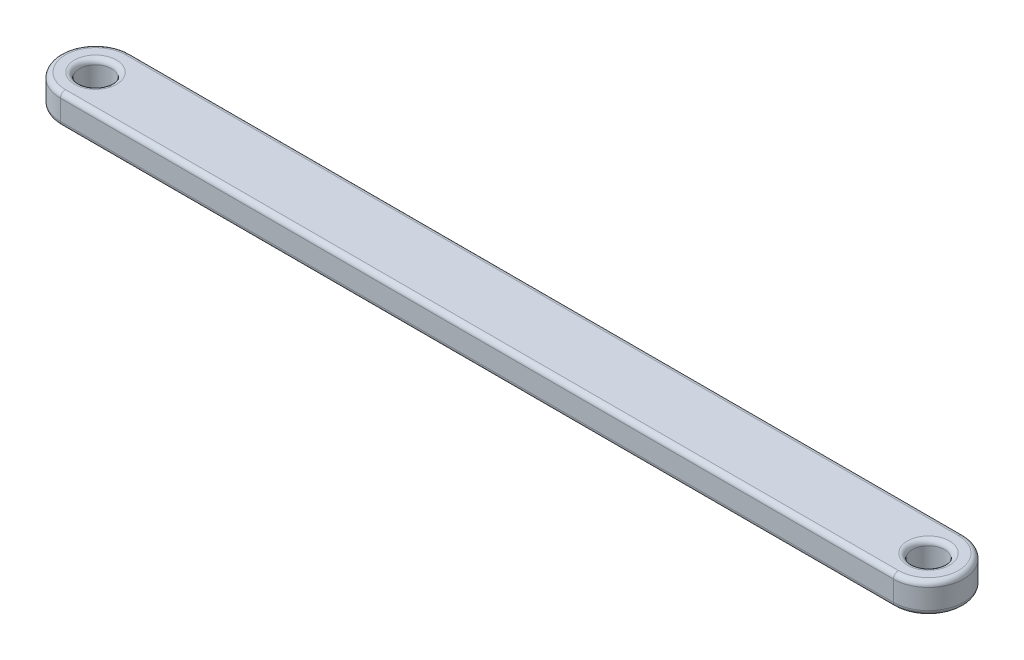
SolidWorks part; units mm, degrees
ref_plane "Front Plane" through (0, 0, 0) normal (0, 0, 1) x (1, 0, 0)
ref_plane "Top Plane" through (0, 0, 0) normal (0, 1, 0) x (1, 0, 0)
ref_plane "Right Plane" through (0, 0, 0) normal (1, 0, 0) x (0, 0, -1)
sketch "Sketch1" plane through (0, 0, 0) normal (0, 1, 0) x (1, 0, 0)
  line L0 (-41.55, 0) -> (41.55, 0) construction
  line L1 (-41.55, 3.5) -> (41.55, 3.5)
  line L2 (-41.55, -3.5) -> (41.55, -3.5)
  arc A0 (-41.55, 3.5) -> (-41.55, -3.5) centre (-41.55, 0) ccw
  arc A1 (41.55, -3.5) -> (41.55, 3.5) centre (41.55, 0) ccw
  circle A2 centre (41.55, 0) radius 1.6
  circle A3 centre (-41.55, 0) radius 1.6
  point P3 (0, 0)
  dimension "D2" = 3.2
  dimension "D1" = 83.1
  dimension "D3" = 7
extrude "Boss-Extrude1" add sketch "Sketch1" along normal blind 3
fillet "Fillet1" radius 0.5 12 edges at (-41.55, 0, 1.6) (41.55, 0, 1.6) (0, 0, 3.5) (45.05, 0, 0) (0, 0, -3.5) (-45.05, 0, 0) (-41.55, 3, 1.6) (0, 3, -3.5) (45.05, 3, 0) (0, 3, 3.5) (-45.05, 3, 0) (41.55, 3, 1.6)
